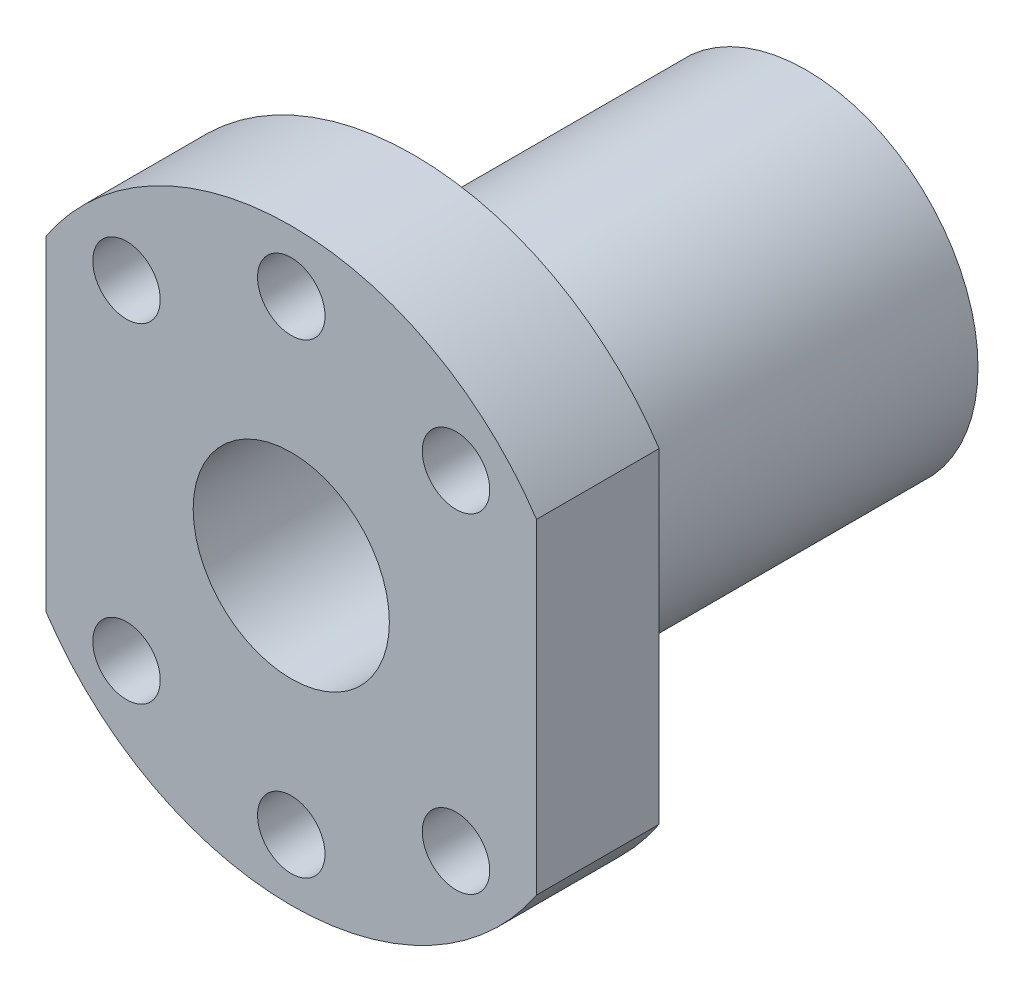
SolidWorks part; units mm, degrees
ref_plane "Plan de face" through (0, 0, 0) normal (0, 0, 1) x (1, 0, 0)
ref_plane "Plan de dessus" through (0, 0, 0) normal (0, 1, 0) x (1, 0, 0)
ref_plane "Plan de droite" through (0, 0, 0) normal (1, 0, 0) x (0, 0, -1)
sketch "Esquisse1" plane through (0, 0, 0) normal (0, 0, 1) x (1, 0, 0)
  circle A0 centre (0, 0) radius 8
  circle A1 centre (0, 0) radius 14
  dimension "D1" = 16
  dimension "D2" = 28
extrude "Boss.-Extru.1" add sketch "Esquisse1" along normal blind 32
sketch "Esquisse2" plane through (0, 0, 32) normal (0, 0, 1) x (1, 0, 0)
  line L0 (20, 13.2665) -> (20, -13.2665)
  line L1 (-20, 13.2665) -> (-20, -13.2665)
  line L2 (-20, 0) -> (20, 0) construction
  circle A0 centre (0, 0) radius 8 construction
  circle A1 centre (0, 0) radius 8
  arc A2 (-20, 13.2665) -> (20, 13.2665) centre (0, 0) cw
  arc A3 (-20, -13.2665) -> (20, -13.2665) centre (0, 0) ccw
  circle A4 centre (0, 0) radius 19 construction
  circle A5 centre (0, 19) radius 2.75
  circle A6 centre (-13.435, 13.435) radius 2.75
  circle A7 centre (13.435, 13.435) radius 2.75
  circle A8 centre (0, -19) radius 2.75
  circle A9 centre (13.435, -13.435) radius 2.75
  circle A10 centre (-13.435, -13.435) radius 2.75
  point P4 (0, 0)
  point P10 (-20, 0)
  point P11 (20, 0)
  dimension "D2" = 24
  dimension "D3" = 38
  dimension "D4" = 5.5
  dimension "D1" = 40
  dimension "D5" = 45
  dimension "D6" = 45
  dimension "D7" = 45
  dimension "D8" = 45
extrude "Boss.-Extru.2" add sketch "Esquisse2" along normal blind 10
